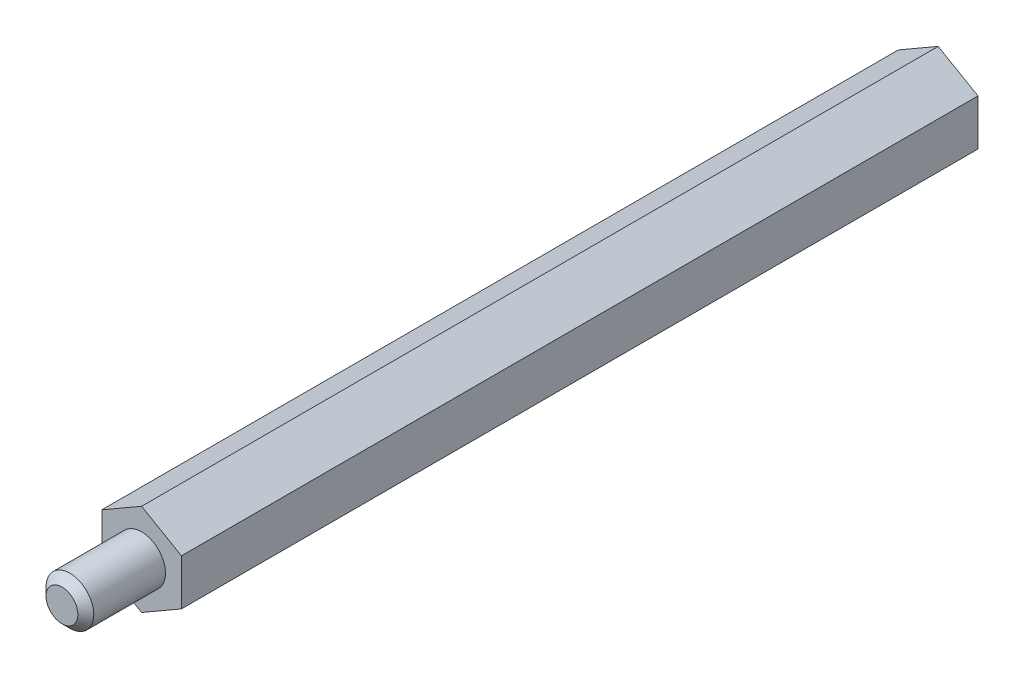
SolidWorks part; units mm, degrees
ref_plane "Front" through (0, 0, 0) normal (0, 0, 1) x (1, 0, 0)
ref_plane "Top" through (0, 0, 0) normal (0, 1, 0) x (1, 0, 0)
ref_plane "Right" through (0, 0, 0) normal (1, 0, 0) x (0, 0, -1)
sketch "Esquisse1" plane through (0, 0, 0) normal (0, 0, 1) x (1, 0, 0)
  line L1 (2.5, -1.4434) -> (2.5, 1.4434)
  line L2 (2.5, 1.4434) -> (0, 2.8868)
  line L3 (0, 2.8868) -> (-2.5, 1.4434)
  line L4 (-2.5, 1.4434) -> (-2.5, -1.4434)
  line L5 (-2.5, -1.4434) -> (0, -2.8868)
  line L6 (0, -2.8868) -> (2.5, -1.4434)
  circle A0 centre (0, 0) radius 2.5 construction
  dimension "D1" = 5
extrude "Boss.-Extru.1" add sketch "Esquisse1" along normal blind 50
sketch "Esquisse2" plane through (0, 0, 50) normal (0, 0, 1) x (1, 0, 0)
  circle A0 centre (0, 0) radius 1.5
  dimension "D1" = 3
extrude "Boss.-Extru.2" add sketch "Esquisse2" along normal blind 5
sketch "Esquisse3" plane through (0, 0, 0) normal (0, 0, -1) x (-1, 0, 0)
  circle A0 centre (0, 0) radius 1.25
  dimension "D1" = 2.5
extrude "Enlèv. mat.-Extru.1" cut sketch "Esquisse3" against normal blind 10
chamfer "Chanfrein1" distance 0.5 angle 45 1 edges at (1.5, 0, 55)
